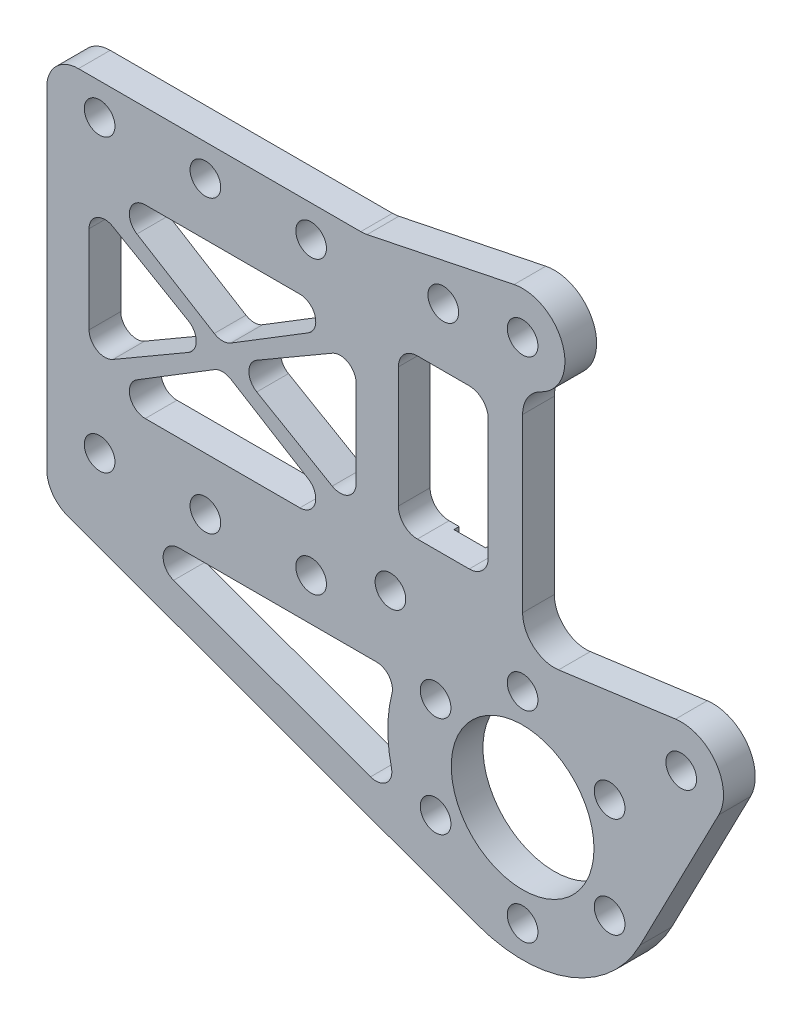
SolidWorks part; units mm, degrees
material "Thornel Mat VMA"
ref_plane "前视基准面" through (0, 0, 0) normal (0, 0, 1) x (1, 0, 0)
ref_plane "上视基准面" through (0, 0, 0) normal (0, 1, 0) x (1, 0, 0)
ref_plane "右视基准面" through (0, 0, 0) normal (1, 0, 0) x (0, 0, -1)
sketch "草图1" plane through (0, 0, 0) normal (0, 0, 1) x (1, 0, 0)
  line L0 (-20, -19) -> (20, -19)
  line L1 (-20, -20) -> (20, -20)
  line L2 (-20, -20) -> (-20, 20)
  line L3 (-20, 20) -> (20, 20)
  line L4 (20, -20) -> (20, 20)
  line L5 (-20, -20) -> (20, 20) construction
  line L6 (-20, 20) -> (20, -20) construction
  line L7 (-20, 15) -> (20, 15) construction
  line L8 (-20, 15) -> (-20, -5) construction
  line L9 (-20, -5) -> (20, -5) construction
  line L10 (20, 15) -> (20, -5) construction
  line L11 (-20, 25) -> (20, 25) construction
  line L12 (-20, 25) -> (-20, -35) construction
  line L13 (-20, -35) -> (20, -35) construction
  line L14 (20, 25) -> (20, -35) construction
  line L15 (-20, -34) -> (20, -34) construction
  line L16 (-20, -19.5) -> (20, -19.5)
  line L17 (-20, -7.89) -> (20, -7.89)
  line L18 (-20, -5.5) -> (20, -5.5)
  line L19 (20, -5) -> (51.2553, -5)
  circle A0 centre (35, -19.5) radius 12.5
  point P0 (0, 0)
  dimension "D5" = 25
  dimension "D6" = 15
  dimension "D1" = 40
  dimension "D2" = 40
  dimension "D3" = 20
  dimension "D4" = 5
  dimension "D7" = 60
  dimension "D8" = 5
  dimension "D9" = 1
  dimension "D10" = 1
  dimension "D11" = 0.5
  dimension "D12" = 14
  dimension "D13" = 2.39
sketch "草图2" plane through (0, 0, 0) normal (0, 0, 1) x (1, 0, 0)
  line L0 (-10, -7) -> (-10, -16.4236)
  line L4 (-20, -20) -> (20, -20) construction
  line L5 (-10, -16.4236) -> (30.7247, -31.2462)
  line L6 (-10, -7) -> (35, -7)
  line L7 (-10, -10.5) -> (20, -10.5) construction
  line L8 (20, -20) -> (20, 20) construction
  line L9 (-10, -10.5) -> (20, -10.5) construction
  line L10 (-10, -16) -> (20, -16) construction
  line L11 (-20, -5.5) -> (20, -5.5) construction
  circle A0 centre (35, -19.5) radius 6.75
  circle A1 centre (35, -19.5) radius 12.5 construction
  arc A2 (35, -7) -> (30.7247, -31.2462) centre (35, -19.5) cw
  circle A3 centre (15, -10.5) radius 1.45
  circle A4 centre (5, -10.5) radius 1.45
  circle A5 centre (-5, -10.5) radius 1.45
  dimension "D1" = 13.5
  dimension "D3" = 5
  dimension "D7" = 20
  dimension "D8" = 15
  dimension "D9" = 10
  dimension "D11" = 45
  dimension "D12" = 2.9
  dimension "D2" = 5
  dimension "D5" = 4
  dimension "D6" = 9.5
extrude "凸台-拉伸1" add sketch "草图2" along normal blind 3
sketch "草图4" plane through (0, 0, 3) normal (0, 0, 1) x (1, 0, 0)
  line L0 (20, -5) -> (51.2553, -5) construction
  line L1 (35, -7) -> (49.4618, -5.0364)
  line L2 (46.103, -25.2423) -> (53.5529, -10.8375)
  circle A0 centre (50, -9) radius 4 construction
  circle A1 centre (50, -9) radius 1.45
  circle A2 centre (35, -19.5) radius 12.5 construction
  arc A3 (49.4618, -5.0364) -> (53.5529, -10.8375) centre (50, -9) cw
  arc A4 (35, -7) -> (46.103, -25.2423) centre (35, -19.5) cw
  dimension "D1" = 8
  dimension "D2" = 2.9
  dimension "D3" = 15
extrude "凸台-拉伸2" add sketch "草图4" against normal blind 3
sketch "草图5" plane through (0, 0, 0) normal (0, 0, -1) x (-1, 0, 0)
  line L0 (-20, 15) -> (-35, 15) construction
  line L1 (-20, -20) -> (-20, 20) construction
  line L2 (-35, -7) -> (-35, 15)
  line L3 (-34.1945, 22.9181) -> (-20, 20)
  line L4 (-20, 20) -> (10, 20)
  line L5 (20, 20) -> (-20, 20) construction
  line L6 (10, -7) -> (10, -16.4236) construction
  line L7 (10, 20) -> (10, -7)
  line L8 (10, -7) -> (-35, -7)
  line L10 (-31.75, 12.5) -> (-23.25, 12.5)
  line L11 (-31.75, 12.5) -> (-31.75, -2.5)
  line L12 (-31.75, -2.5) -> (-23.25, -2.5)
  line L13 (-23.25, 12.5) -> (-23.25, -2.5)
  circle A0 centre (-35, 19) radius 4 construction
  circle A1 centre (-35, 19) radius 1.45
  arc A2 (-35, 15) -> (-34.1945, 22.9181) centre (-35, 19) cw
  dimension "D2" = 8
  dimension "D3" = 2.9
  dimension "D1" = 15
  dimension "D4" = 15
  dimension "D5" = 8.5
  dimension "D6" = 15
  dimension "D7" = 3.25
  dimension "D8" = 2.5
extrude "凸台-拉伸3" add sketch "草图5" against normal blind 3
sketch "草图7" plane through (0, 0, 3) normal (0, 0, 1) x (1, 0, 0)
  line L0 (23.25, 5) -> (31.75, 5) construction
  line L1 (23.25, -2.5) -> (23.25, 12.5) construction
  line L2 (31.75, 12.5) -> (31.75, -2.5) construction
  line L3 (27.5, 5) -> (27.5, 18) construction
  line L4 (-20, 20) -> (20, 20) construction
  line L5 (-5, -10.5) -> (-5, 0) construction
  line L6 (5, -10.5) -> (5, 0) construction
  line L7 (15, -10.5) -> (15, 0) construction
  line L8 (27.5, -8) -> (22.5, -8) construction
  circle A0 centre (27.5, 18) radius 1.45
  circle A1 centre (27.5, -8) radius 1.45 construction
  circle A2 centre (-5, 17) radius 1.45
  circle A3 centre (5, 17) radius 1.45
  circle A4 centre (15, 17) radius 1.45
  circle A5 centre (22.5, -8) radius 1.45
  dimension "D2" = 2.9
  dimension "D3" = 3
  dimension "D4" = 2.9
  dimension "D1" = 13
  dimension "D5" = 5
extrude "切除-拉伸3" cut sketch "草图7" against normal blind 20
fillet "圆角1" radius 1.8 4 edges at (23.25, -2.5, 1.5) (31.75, -2.5, 1.5) (31.75, 12.5, 1.5) (23.25, 12.5, 1.5)
fillet "圆角2" radius 3 5 edges at (-10, -16.4236, 1.5) (-10, 20, 1.5) (35, 15, 1.5) (35, -7, 1.5) (20, 20, 1.5)
sketch "草图9" plane through (0, 0, 0) normal (0, 0, -1) x (-1, 0, 0)
  line L0 (-23.25, -0.7) -> (-23.25, 10.7) construction
  line L1 (-20.25, 13) -> (7, 13) construction
  line L2 (-20.25, 13) -> (-20.25, -6.5) construction
  line L3 (-20.25, -6.5) -> (7, -6.5) construction
  line L4 (7, 13) -> (7, -6.5) construction
  line L5 (10, 17) -> (10, -14.3229) construction
  line L6 (-20.25, 3.25) -> (7, 3.25) construction
  line L7 (-6.625, 13) -> (-6.625, -6.5) construction
  line L8 (-6.625, 4.25) -> (-19.25, 12)
  line L9 (-19.25, 12) -> (6, 12)
  line L10 (6, 12) -> (-6.625, 4.25)
  line L11 (-7.625, 3.25) -> (-19.25, 10)
  line L12 (-19.25, 10) -> (-19.25, -3.5)
  line L13 (-19.25, -3.5) -> (-7.625, 3.25)
  line L14 (6, 10) -> (6, -3.5)
  line L15 (-5.625, 3.25) -> (6, 10)
  line L16 (6, -3.5) -> (-5.625, 3.25)
  line L17 (-19.25, -5.5) -> (6, -5.5)
  line L18 (-6.625, 2.25) -> (-19.25, -5.5)
  line L19 (6, -5.5) -> (-6.625, 2.25)
  line L20 (-23.2713, -14.5) -> (6, -14.5)
  line L21 (6, -14.5) -> (-23.6394, -25.2879)
  line L22 (8.0261, -17.142) -> (-30.7247, -31.2462) construction
  line L23 (-35, -19.5) -> (-35, -10) construction
  line L24 (-35, -19.5) -> (-26.7728, -14.75) construction
  circle A0 centre (-15, 17) radius 1.45 construction
  circle A1 centre (-5, -10.5) radius 1.45 construction
  circle A2 centre (-15, -10.5) radius 1.45 construction
  arc A3 (-23.2713, -14.5) -> (-23.6394, -25.2879) centre (-35, -19.5) cw
  circle A4 centre (-35, -19.5) radius 6.75 construction
  circle A5 centre (-35, -19.5) radius 9.5 construction
  circle A6 centre (-26.7728, -14.75) radius 1.45
  circle A7 centre (-26.7728, -24.25) radius 1.45
  circle A8 centre (-35, -29) radius 1.45
  circle A9 centre (-43.2272, -24.25) radius 1.45
  circle A10 centre (-43.2272, -14.75) radius 1.45
  circle A11 centre (-35, -10) radius 1.45
  dimension "D15" = 6
  dimension "D16" = 19
  dimension "D18" = 2.9
  dimension "D1" = 4
  dimension "D2" = 3
  dimension "D3" = 4
  dimension "D4" = 3
  dimension "D5" = 1
  dimension "D6" = 1
  dimension "D7" = 1
  dimension "D8" = 1
  dimension "D9" = 1
  dimension "D10" = 1
  dimension "D11" = 3
  dimension "D12" = 3
  dimension "D13" = 4
  dimension "D14" = 4
  dimension "D17" = 60
  dimension "D19" = 6
extrude "切除-拉伸5" cut sketch "草图9" against normal blind 10.5
fillet "圆角3" radius 1.5 15 edges at (-6, -14.5, 1.5) (23.6394, -25.2879, 1.5) (23.2713, -14.5, 1.5) (-6, -5.5, 1.5) (19.25, -5.5, 1.5) (6.625, 2.25, 1.5) (-6, -3.5, 1.5) (-6, 10, 1.5) (5.625, 3.25, 1.5) (19.25, 12, 1.5) (-6, 12, 1.5) (6.625, 4.25, 1.5) (19.25, 10, 1.5) (7.625, 3.25, 1.5) (19.25, -3.5, 1.5)
sketch "草图10" plane through (0, 0, 0) normal (0, 0, -1) x (-1, 0, 0)
  line L0 (-27.5, 12.5) -> (-27.5, -2.5) construction
  line L1 (-25.05, 12.5) -> (-29.95, 12.5) construction
  line L2 (-29.95, -2.5) -> (-25.05, -2.5) construction
  line L4 (-29, -5) -> (-26, -5)
  line L5 (-29, -5) -> (-29, 15)
  line L6 (-29, 15) -> (-26, 15)
  line L7 (-26, -5) -> (-26, 15)
  line L8 (-29, -5) -> (-26, 15) construction
  line L9 (-29, 15) -> (-26, -5) construction
  point P6 (-27.5, 5)
  dimension "D1" = 3
  dimension "D2" = 20
extrude "切除-拉伸6" cut sketch "草图10" against normal blind 0.5
sketch "草图11" plane through (0, 0, 0) normal (0, 0, -1) x (-1, 0, 0)
  line L0 (-29, 15) -> (-29, 12.5) construction
  line L1 (-26, 12.5) -> (-26, 15) construction
  line L2 (-29, -2.5) -> (-29, -5) construction
  line L3 (-26, -5) -> (-26, -2.5) construction
  circle A0 centre (-29, 14.1) radius 0.9
  circle A1 centre (-26, 14.1) radius 0.9
  circle A2 centre (-29, -4.1) radius 0.9
  circle A3 centre (-26, -4.1) radius 0.9
  dimension "D1" = 1.8
  dimension "D2" = 1.8
  dimension "D3" = 1.8
  dimension "D4" = 1.8
extrude "切除-拉伸7" cut sketch "草图11" against normal blind 0.5
